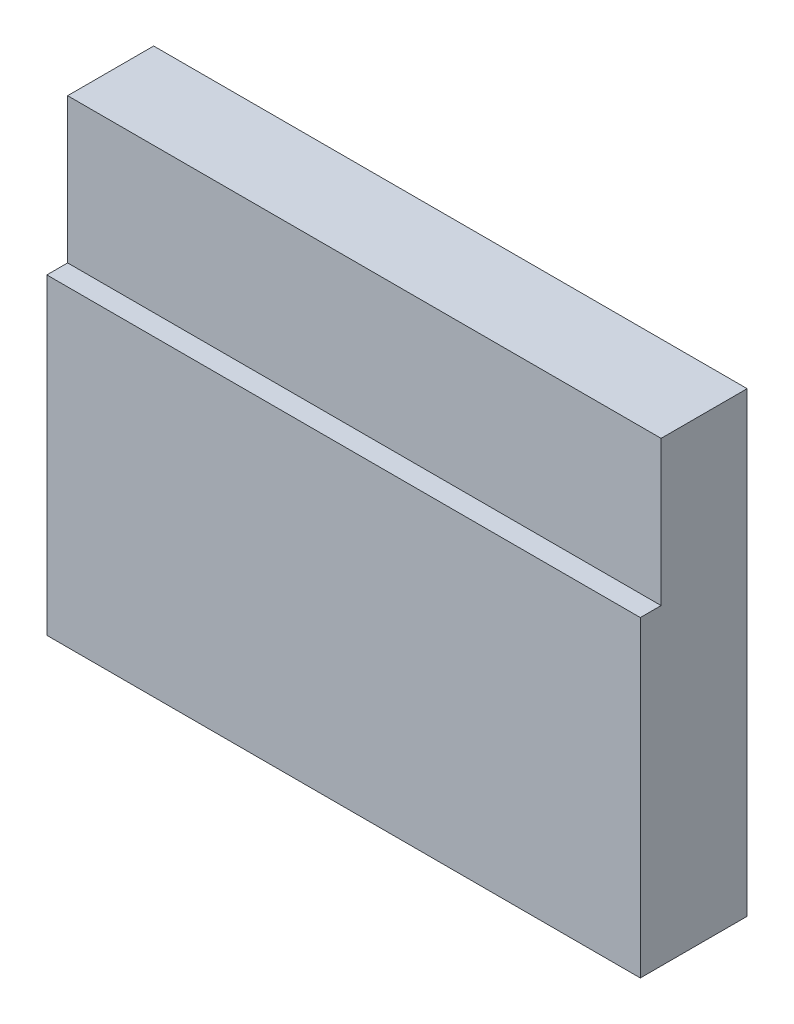
SolidWorks part; units mm, degrees
ref_plane "Front Plane" through (0, 0, 0) normal (0, 0, 1) x (1, 0, 0)
ref_plane "Top Plane" through (0, 0, 0) normal (0, 1, 0) x (1, 0, 0)
ref_plane "Right Plane" through (0, 0, 0) normal (1, 0, 0) x (0, 0, -1)
ref_plane "Plane1" through (0, 0, -10) normal (0, 0, 1) x (1, 0, 0)
sketch "Sketch2" plane through (0, 0, -10) normal (0, 0, 1) x (1, 0, 0)
  line L0 (0, 59) -> (0, 0) construction
  line L1 (-5, 72) -> (95, 72)
  line L2 (-5, 72) -> (-5, -5)
  line L3 (-5, -5) -> (95, -5)
  line L4 (95, 72) -> (95, -5)
  line L5 (90, 67) -> (0, 67) construction
  line L6 (90, 0) -> (90, 67) construction
  line L7 (0, 0) -> (90, 0) construction
  dimension "D1" = 5
  dimension "D2" = 5
  dimension "D3" = 5
  dimension "D4" = 5
extrude "Boss-Extrude1" add sketch "Sketch2" along normal blind 18
sketch "Sketch3" plane through (0, 0, 8) normal (0, 0, 1) x (1, 0, 0)
  line L0 (95, -5) -> (95, 72) construction
  line L1 (-5, 72) -> (95, 72)
  line L2 (-5, 72) -> (-5, 47.5975)
  line L3 (-5, 47.5975) -> (95, 47.5975)
  line L4 (95, 72) -> (95, 47.5975)
extrude "Cut-Extrude1" cut sketch "Sketch3" against normal blind 3.5
